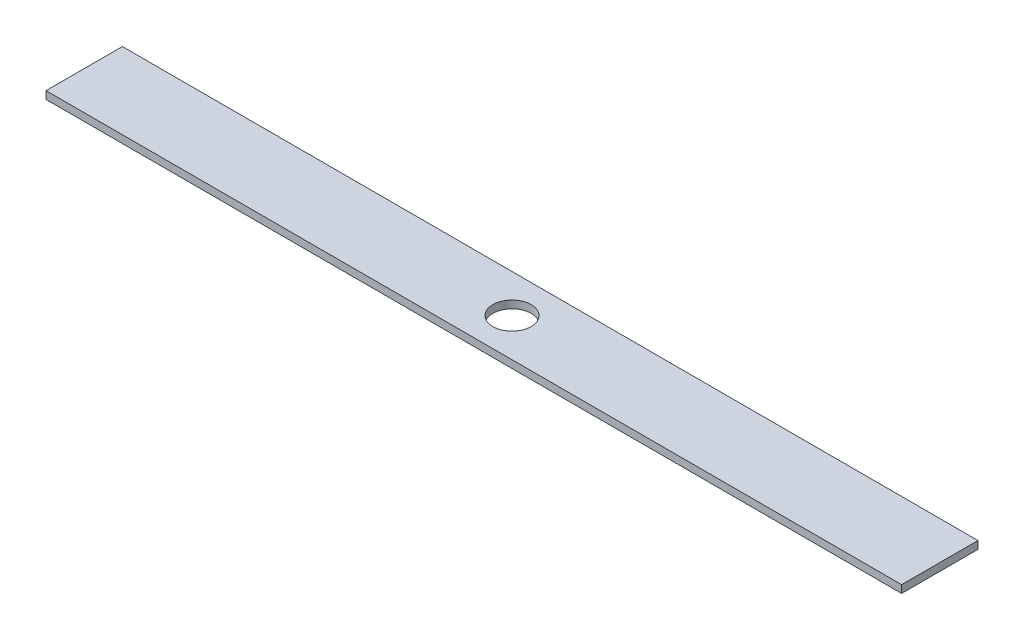
SolidWorks part; units mm, degrees
ref_plane "Front Plane" through (0, 0, 0) normal (0, 0, 1) x (1, 0, 0)
ref_plane "Top Plane" through (0, 0, 0) normal (0, 1, 0) x (1, 0, 0)
ref_plane "Right Plane" through (0, 0, 0) normal (1, 0, 0) x (0, 0, -1)
sketch "Sketch1" plane through (0, 0, 0) normal (0, 1, 0) x (1, 0, 0)
  line L1 (-177.8, -15.875) -> (177.8, -15.875)
  line L2 (-177.8, -15.875) -> (-177.8, 15.875)
  line L3 (-177.8, 15.875) -> (177.8, 15.875)
  line L4 (177.8, -15.875) -> (177.8, 15.875)
  line L5 (-177.8, -15.875) -> (177.8, 15.875) construction
  line L6 (-177.8, 15.875) -> (177.8, -15.875) construction
  circle A0 centre (0, 0) radius 7.9375
  dimension "D3" = 15.875
  dimension "D1" = 355.6
  dimension "D2" = 31.75
extrude "Boss-Extrude1" add sketch "Sketch1" along normal blind 3.175
